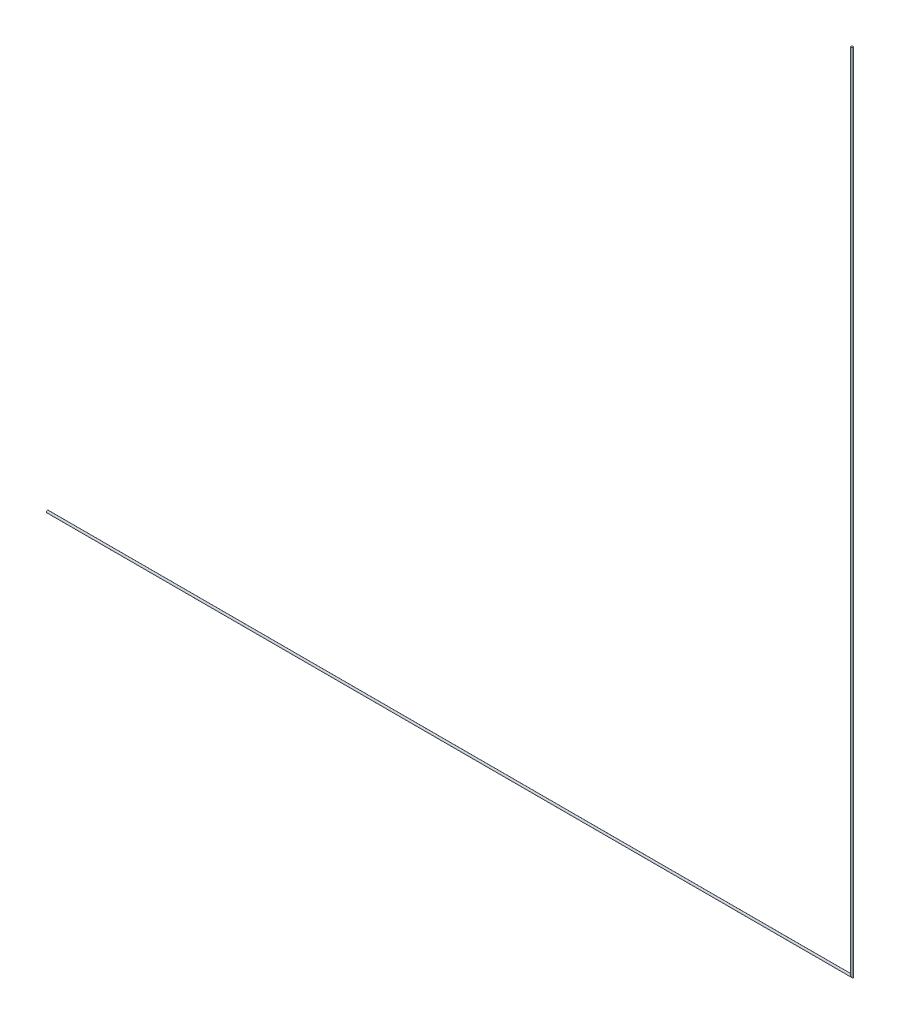
SolidWorks part; units mm, degrees
ref_plane "正面" through (0, 0, 0) normal (0, 0, 1) x (1, 0, 0)
ref_plane "平面" through (0, 0, 0) normal (0, 1, 0) x (1, 0, 0)
ref_plane "右側面" through (0, 0, 0) normal (1, 0, 0) x (0, 0, -1)
sketch "ｽｹｯﾁ1" plane through (0, 0, 0) normal (0, 0, 1) x (1, 0, 0)
  line L0 (0, 0) -> (762, 0)
  line L1 (762, 762) -> (762, 0)
  dimension "D1" = 762
  dimension "D2" = 762
sketch "ｽｹｯﾁ3" plane through (0, 0, 0) normal (1, 0, 0) x (0, 0, -1)
  circle A0 centre (0, 0) radius 1
  dimension "D1" = 2
sweep "ｽｲｰﾌﾟ1" add profiles "ｽｹｯﾁ3" path "ｽｹｯﾁ1"
